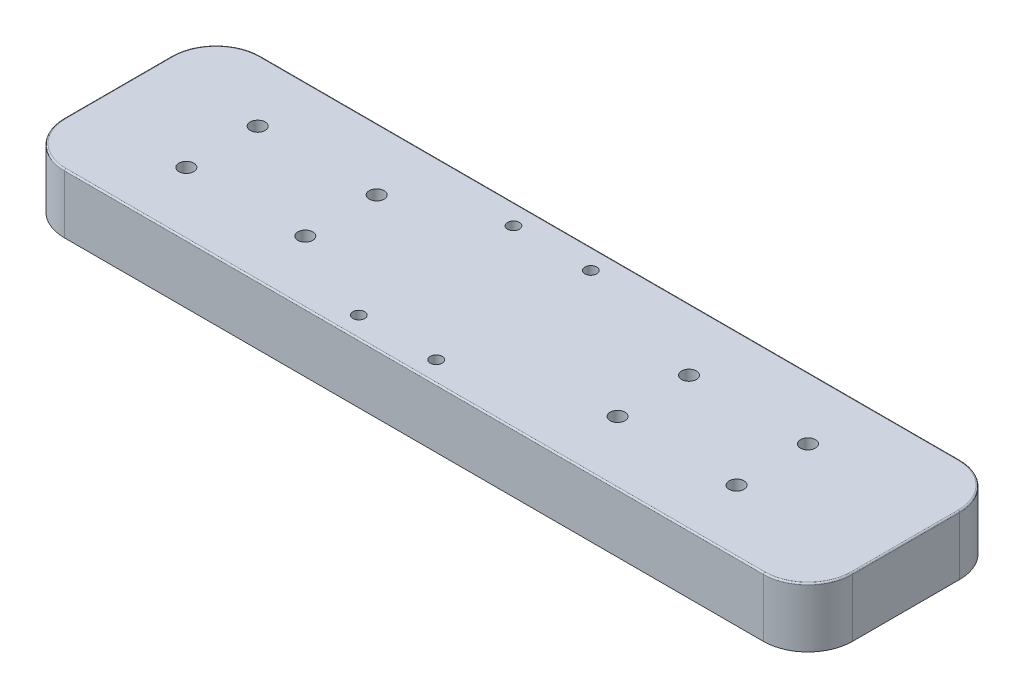
SolidWorks part; units mm, degrees
material "1060 Alloy"
ref_plane "Front Plane" through (0, 0, 0) normal (0, 0, 1) x (1, 0, 0)
ref_plane "Top Plane" through (0, 0, 0) normal (0, 1, 0) x (1, 0, 0)
ref_plane "Right Plane" through (0, 0, 0) normal (1, 0, 0) x (0, 0, -1)
sketch "Sketch1" plane through (0, 0, 0) normal (0, 1, 0) x (1, 0, 0)
  line L1 (-2984.5, 838.2) -> (2984.5, 838.2)
  line L2 (-3365.5, 457.2) -> (-3365.5, -457.2)
  line L3 (-2984.5, -838.2) -> (2984.5, -838.2)
  line L4 (3365.5, 457.2) -> (3365.5, -457.2)
  line L5 (-3365.5, 838.2) -> (3365.5, -838.2) construction
  line L6 (-3365.5, -838.2) -> (3365.5, 838.2) construction
  arc A0 (2984.5, -838.2) -> (3365.5, -457.2) centre (2984.5, -457.2) ccw
  arc A1 (2984.5, 838.2) -> (3365.5, 457.2) centre (2984.5, 457.2) cw
  arc A2 (-2984.5, 838.2) -> (-3365.5, 457.2) centre (-2984.5, 457.2) ccw
  arc A3 (-3365.5, -457.2) -> (-2984.5, -838.2) centre (-2984.5, -457.2) ccw
  point P0 (0, 0)
  dimension "D3" = 381
  dimension "D1" = 6731
  dimension "D2" = 1676.4
extrude "Boss-Extrude1" add sketch "Sketch1" along normal mid plane 508
sketch "Sketch2" plane through (0, -254, 0) normal (0, -1, 0) x (1, 0, 0)
  line L8 (3238.5, -457.2) -> (3238.5, 457.2)
  line L9 (-2984.5, -711.2) -> (2984.5, -711.2)
  line L10 (-3238.5, 457.2) -> (-3238.5, -457.2)
  line L11 (2984.5, 711.2) -> (-2984.5, 711.2)
  line L12 (3238.5, -457.2) -> (3238.5, 457.2)
  line L13 (-2984.5, -711.2) -> (2984.5, -711.2)
  line L14 (-3238.5, 457.2) -> (-3238.5, -457.2)
  line L15 (2984.5, 711.2) -> (-2984.5, 711.2)
  arc A8 (2984.5, -711.2) -> (3238.5, -457.2) centre (2984.5, -457.2) ccw
  arc A9 (3238.5, 457.2) -> (2984.5, 711.2) centre (2984.5, 457.2) ccw
  arc A10 (-3238.5, -457.2) -> (-2984.5, -711.2) centre (-2984.5, -457.2) ccw
  arc A11 (-2984.5, 711.2) -> (-3238.5, 457.2) centre (-2984.5, 457.2) ccw
  arc A12 (2984.5, -711.2) -> (3238.5, -457.2) centre (2984.5, -457.2) ccw
  arc A13 (3238.5, 457.2) -> (2984.5, 711.2) centre (2984.5, 457.2) ccw
  arc A14 (-3238.5, -457.2) -> (-2984.5, -711.2) centre (-2984.5, -457.2) ccw
  arc A15 (-2984.5, 711.2) -> (-3238.5, 457.2) centre (-2984.5, 457.2) ccw
  dimension "D1" = 127
extrude "Cut-Extrude1" cut sketch "Sketch2" against normal blind 381
sketch "Sketch3" plane through (0, 254, 0) normal (0, 1, 0) x (1, 0, 0)
  line L0 (2984.5, 838.2) -> (-2984.5, 838.2) construction
  line L2 (-3365.5, 457.2) -> (-3365.5, -457.2) construction
  line L3 (3365.5, -457.2) -> (3365.5, 457.2) construction
  circle A0 centre (-2476.5, 304.8) radius 63.5
  circle A1 centre (-1460.5, 304.8) radius 63.5
  circle A2 centre (-647.7, 660.4) radius 50.8
  circle A3 centre (12.7, 660.4) radius 50.8
  circle A4 centre (1206.5, 304.8) radius 63.5
  circle A5 centre (2222.5, 304.8) radius 63.5
  circle A6 centre (-2476.5, -304.8) radius 63.5
  circle A7 centre (-1460.5, -304.8) radius 63.5
  circle A8 centre (-647.7, -660.4) radius 50.8
  circle A9 centre (12.7, -660.4) radius 50.8
  circle A10 centre (1206.5, -304.8) radius 63.5
  circle A11 centre (2222.5, -304.8) radius 63.5
  dimension "D1" = 127
  dimension "D11" = 101.6
  dimension "D2" = 533.4
  dimension "D3" = 609.6
  dimension "D4" = 889
  dimension "D5" = 1016
  dimension "D6" = 812.8
  dimension "D7" = 1320.8
  dimension "D8" = 1193.8
  dimension "D9" = 1016
  dimension "D10" = 1143
  dimension "D12" = 177.8
extrude "Cut-Extrude2" cut sketch "Sketch3" against normal up to surface (127 mm away) up to face at (0, 127, 0)
fillet "Fillet1" radius 12.7 16 edges at (3164.1051, -254, -636.8051) (0, -254, -711.2) (-3164.1051, -254, -636.8051) (-3238.5, -254, 0) (-3164.1051, -254, 636.8051) (0, -254, 711.2) (3164.1051, -254, 636.8051) (-3253.9077, 254, 726.6077) (-3365.5, 254, 0) (-3253.9077, 254, -726.6077) (0, 254, -838.2) (3253.9077, 254, -726.6077) (3365.5, 254, 0) (3253.9077, 254, 726.6077) (3238.5, -254, 0) (0, 254, 838.2)
